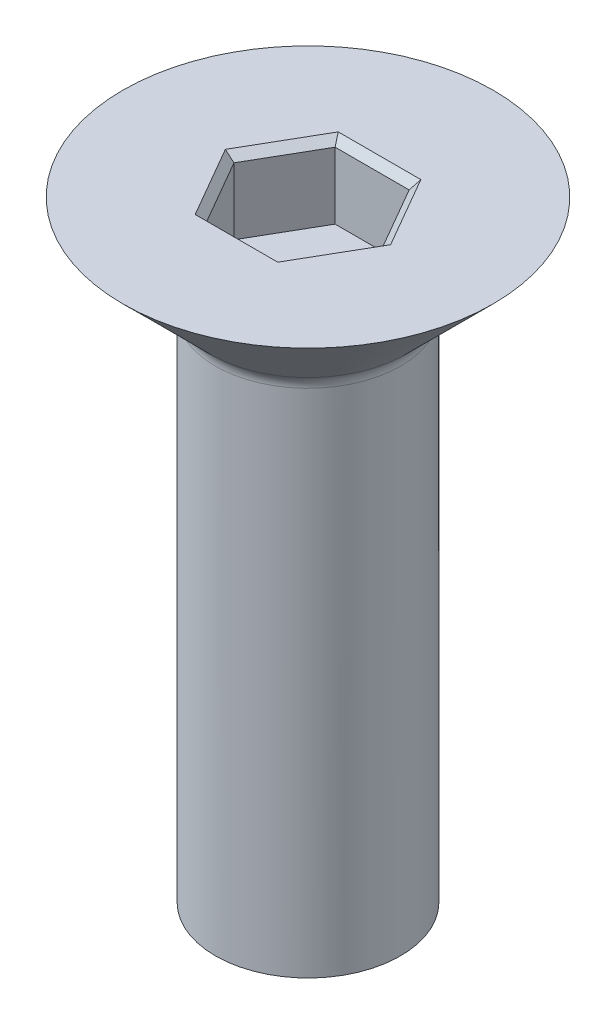
SolidWorks part; units mm, degrees
ref_plane "Front Plane" through (0, 0, 0) normal (0, 0, 1) x (1, 0, 0)
ref_plane "Top Plane" through (0, 0, 0) normal (0, 1, 0) x (1, 0, 0)
ref_plane "Right Plane" through (0, 0, 0) normal (1, 0, 0) x (0, 0, -1)
sketch "Sketch1" plane through (0, 0, 0) normal (0, 1, 0) x (1, 0, 0)
  circle A0 centre (0, 0) radius 2.5
  dimension "D1" = 5
extrude "Boss-Extrude1" add sketch "Sketch1" along normal blind 14 contours A0
sketch "Sketch2" plane through (0, 0, 0) normal (0, 0, 1) x (1, 0, 0)
  line L3 (-5, 16.5) -> (-2.5, 14)
  line L4 (0, 14) -> (0, 16.5)
  line L5 (-5, 16.5) -> (0, 16.5)
  line L6 (-2.5, 14) -> (0, 14)
revolve "Revolve1" add sketch "Sketch2" angle 360 about L4
sketch "Sketch3" plane through (0, 16.5, 0) normal (0, 1, 0) x (1, 0, 0)
  line L8 (2, 0) -> (1, 1.7321)
  line L9 (1, 1.7321) -> (-1, 1.7321)
  line L10 (-1, 1.7321) -> (-2, 0)
  line L11 (-2, 0) -> (-1, -1.7321)
  line L12 (-1, -1.7321) -> (1, -1.7321)
  line L13 (1, -1.7321) -> (2, 0)
  circle A0 centre (0, 0) radius 1.7321 construction
  dimension "D1" = 2
extrude "Cut-Extrude1" cut sketch "Sketch3" against normal blind 2
chamfer "Chamfer1" distance 0.2 6 edges at (-1.5, 16.5, -0.866) (-1.5, 16.5, 0.866) (0, 16.5, 1.7321) (1.5, 16.5, 0.866) (1.5, 16.5, -0.866) (0, 16.5, -1.7321)
fillet "Fillet1" radius 0.5 1 edges at (0, 14, 2.5)
